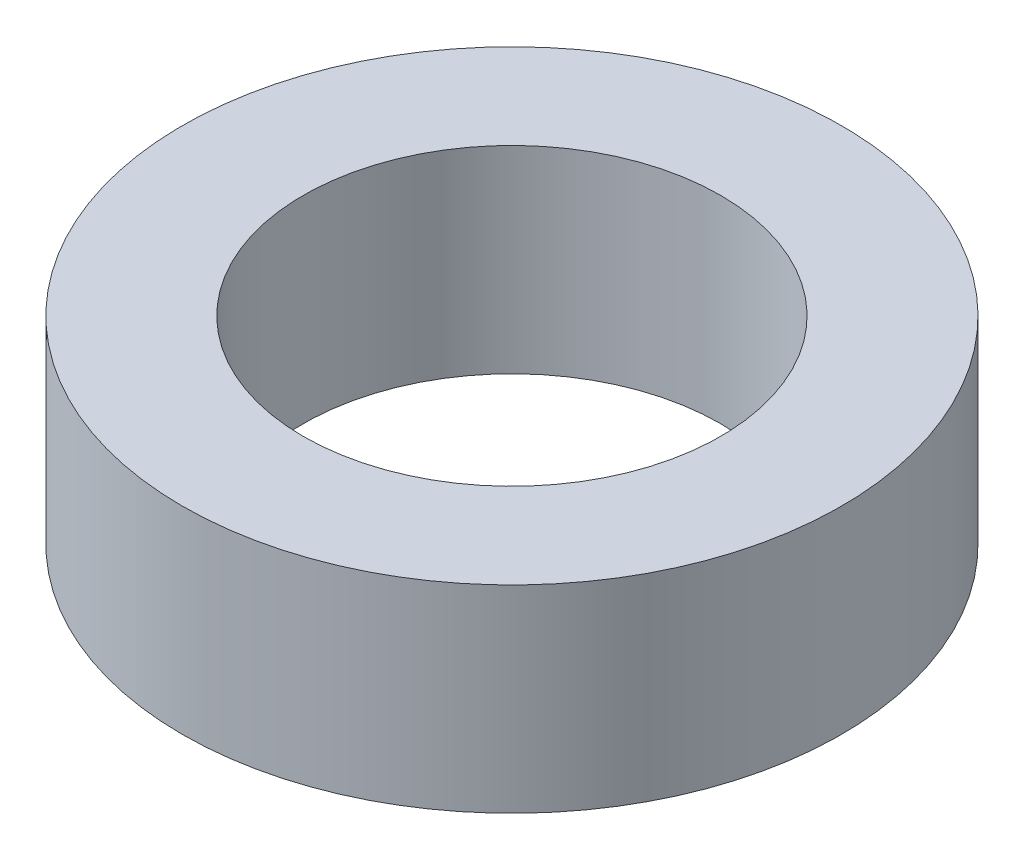
SolidWorks part; units mm, degrees
ref_plane "Front Plane" through (0, 0, 0) normal (0, 0, 1) x (1, 0, 0)
ref_plane "Top Plane" through (0, 0, 0) normal (0, 1, 0) x (1, 0, 0)
ref_plane "Right Plane" through (0, 0, 0) normal (1, 0, 0) x (0, 0, -1)
sketch "Sketch1" plane through (0, 0, 0) normal (0, 1, 0) x (1, 0, 0)
  circle A0 centre (0, 0) radius 15
extrude "Boss-Extrude1" add sketch "Sketch1" along normal blind 9
sketch "Sketch5" plane through (0, 9, 0) normal (0, 1, 0) x (1, 0, 0)
  circle A0 centre (0, 0) radius 9.5
extrude "Cut-Extrude3" cut sketch "Sketch5" against normal through all
